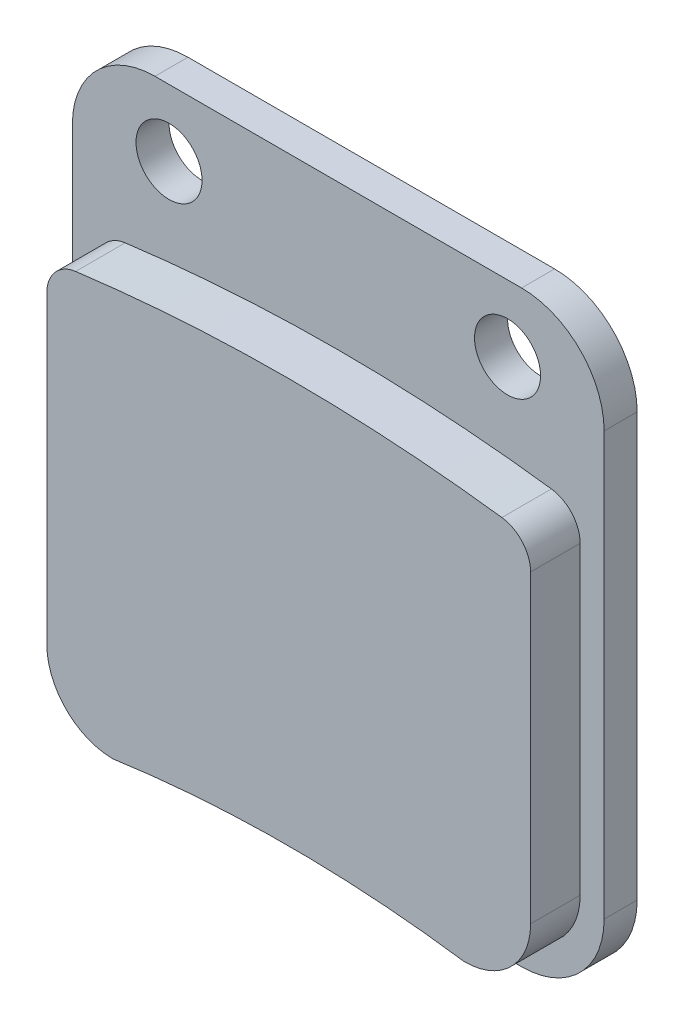
SolidWorks part; units mm, degrees
material "Ceramic Porcelain"
ref_plane "Front Plane" through (0, 0, 0) normal (0, 0, 1) x (1, 0, 0)
ref_plane "Top Plane" through (0, 0, 0) normal (0, 1, 0) x (1, 0, 0)
ref_plane "Right Plane" through (0, 0, 0) normal (1, 0, 0) x (0, 0, -1)
sketch "Sketch1" plane through (0, 0, 0) normal (0, 0, 1) x (1, 0, 0)
  line L0 (0, 0) -> (0, 17.4818) construction
  line L1 (-14.097, -22.606) -> (14.097, -22.606)
  line L2 (-20.447, -16.256) -> (-20.447, 16.256)
  line L3 (-14.097, 22.606) -> (14.097, 22.606)
  line L4 (20.447, -16.256) -> (20.447, 16.256)
  line L5 (-20.447, -22.606) -> (20.447, 22.606) construction
  line L6 (-20.447, 22.606) -> (20.447, -22.606) construction
  line L7 (-13.0175, 17.4818) -> (13.0175, 17.4818) construction
  line L8 (0, 0) -> (0, -5.5789) construction
  circle A0 centre (0, -5.5789) radius 15.875 construction
  circle A1 centre (13.0175, 17.4818) radius 2.54
  circle A2 centre (-13.0175, 17.4818) radius 2.54
  arc A3 (-14.097, -22.606) -> (-20.447, -16.256) centre (-14.097, -16.256) cw
  arc A4 (14.097, -22.606) -> (20.447, -16.256) centre (14.097, -16.256) ccw
  arc A5 (14.097, 22.606) -> (20.447, 16.256) centre (14.097, 16.256) cw
  arc A6 (-20.447, 16.256) -> (-14.097, 22.606) centre (-14.097, 16.256) cw
  point P0 (0, 0)
  dimension "D3" = 31.75
  dimension "D5" = 5.08
  dimension "D6" = 6.35
  dimension "D1" = 45.212
  dimension "D2" = 40.894
  dimension "D4" = 26.035
extrude "Boss-Extrude1" add sketch "Sketch1" along normal blind 2.54
sketch "Sketch2" plane through (0, 0, 2.54) normal (0, 0, 1) x (1, 0, 0)
  line L0 (0, 0) -> (0, -115.57) construction
  line L3 (-18.6033, -15.5838) -> (-18.6033, 7.849)
  line L4 (18.6033, -15.5838) -> (18.6033, 7.849)
  arc A0 (16.3911, 10.3678) -> (-16.3911, 10.3678) centre (0, -115.57) ccw
  arc A1 (13.4724, -20.6566) -> (-13.5233, -20.6638) centre (0, -115.57) ccw
  arc A4 (-18.6033, -15.5838) -> (-13.5233, -20.6638) centre (-13.5233, -15.5838) ccw
  arc A5 (13.4724, -20.6566) -> (18.6033, -15.5838) centre (13.5233, -15.5768) ccw
  arc A6 (18.6033, 7.849) -> (16.3911, 10.3678) centre (16.0633, 7.849) ccw
  arc A7 (-18.6033, 7.849) -> (-16.3911, 10.3678) centre (-16.0633, 7.849) cw
  dimension "D2" = 254
  dimension "D3" = 2.54
  dimension "D1" = 115.57
extrude "Boss-Extrude2" add sketch "Sketch2" along normal blind 3.81
sketch "Sketch3" plane through (0, 0, 6.35) normal (0, 0, 1) x (1, 0, 0)
  arc A0 (16.3911, 10.3678) -> (-16.3911, 10.3678) centre (0, -115.57) ccw construction
  point P0 (0, 11.43)
ref_point "Point1"
ref_plane "Plane1" through (0, 11.43, 6.35) normal (0, 1, 0) x (1, 0, 0)
move or copy body "Body-Move/Copy1" [suppressed] bodies to move or copy 102
